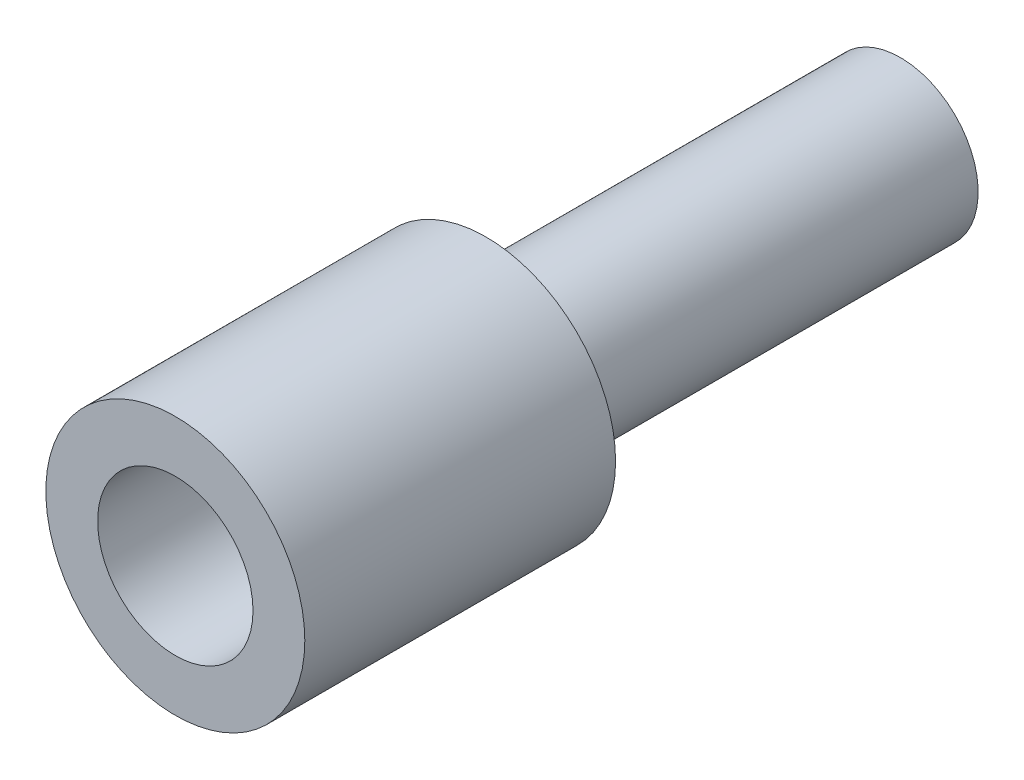
SolidWorks part; units mm, degrees
ref_plane "Plan de face" through (0, 0, 0) normal (0, 0, 1) x (1, 0, 0)
ref_plane "Plan de dessus" through (0, 0, 0) normal (0, 1, 0) x (1, 0, 0)
ref_plane "Plan de droite" through (0, 0, 0) normal (1, 0, 0) x (0, 0, -1)
sketch "Esquisse1" plane through (0, 0, 0) normal (0, 0, 1) x (1, 0, 0)
  circle A0 centre (0, 0) radius 2.5
  dimension "D1" = 5
extrude "Boss.-Extru.1" add sketch "Esquisse1" along normal blind 6
sketch "Esquisse2" plane through (0, 0, 6) normal (0, 0, 1) x (1, 0, 0)
  circle A0 centre (0, 0) radius 1.5
  dimension "D1" = 3
extrude "Enlèv. mat.-Extru.1" cut sketch "Esquisse2" against normal blind 5
sketch "Esquisse3" plane through (0, 0, 0) normal (0, 0, -1) x (-1, 0, 0)
  circle A0 centre (0, 0) radius 1.5
  dimension "D1" = 3
extrude "Boss.-Extru.2" add sketch "Esquisse3" along normal blind 8
